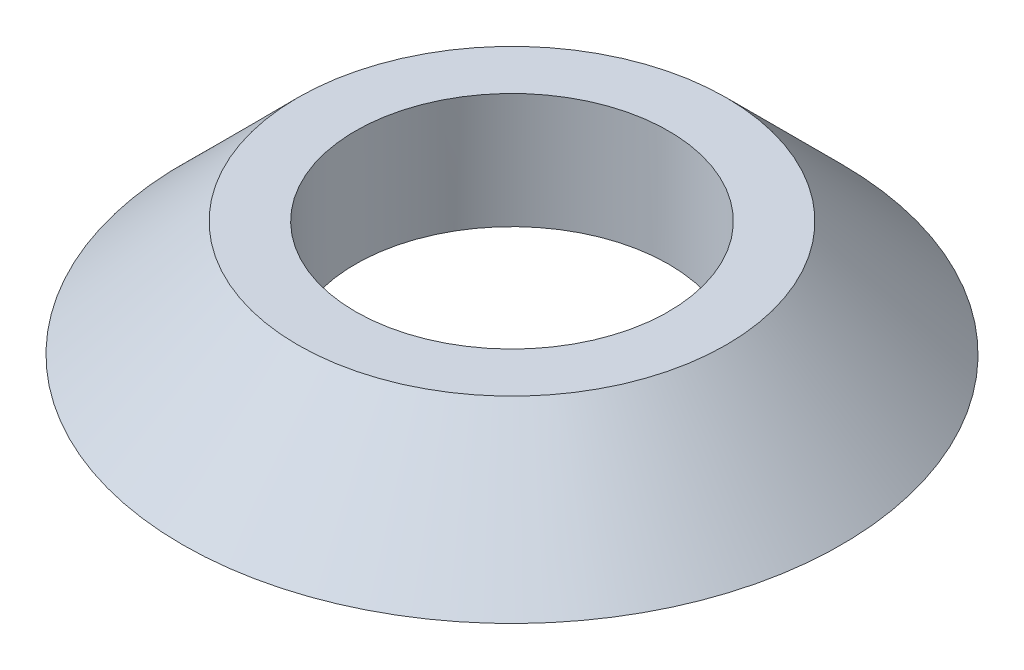
SolidWorks part; units mm, degrees
ref_plane "前视基准面" through (0, 0, 0) normal (0, 0, 1) x (1, 0, 0)
ref_plane "上视基准面" through (0, 0, 0) normal (0, 1, 0) x (1, 0, 0)
ref_plane "右视基准面" through (0, 0, 0) normal (1, 0, 0) x (0, 0, -1)
sketch "草图1" plane through (0, 0, 0) normal (0, 0, 1) x (1, 0, 0)
  line L0 (0, 0) -> (0, 7)
  line L1 (0, 0) -> (20, 0)
  line L2 (0, 7) -> (13, 7)
  line L3 (13, 7) -> (20, 0)
  dimension "D1" = 7
  dimension "D2" = 20
  dimension "D3" = 13
revolve "旋转1" add sketch "草图1" angle 360 about L0
sketch "草图2" plane through (0, 7, 0) normal (0, 1, 0) x (1, 0, 0)
  circle A0 centre (0, 0) radius 9.5
extrude "切除-拉伸1" cut sketch "草图2" against normal blind 10
